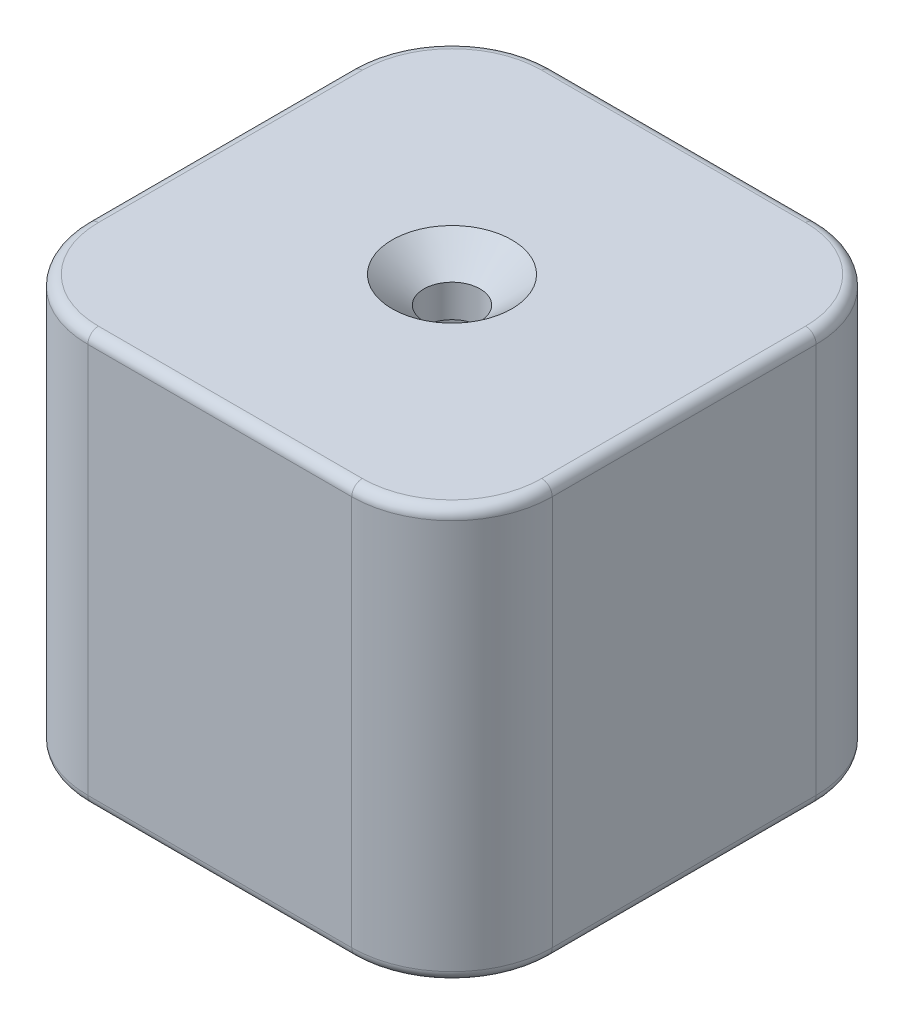
SolidWorks part; units mm, degrees
ref_plane "Front Plane" through (0, 0, 0) normal (0, 0, 1) x (1, 0, 0)
ref_plane "Top Plane" through (0, 0, 0) normal (0, 1, 0) x (1, 0, 0)
ref_plane "Right Plane" through (0, 0, 0) normal (1, 0, 0) x (0, 0, -1)
sketch "Sketch1" plane through (0, 0, 0) normal (0, 1, 0) x (1, 0, 0)
  line L0 (-27.94, -15.875) -> (-27.94, 15.875)
  line L1 (-15.875, -25.4) -> (15.875, -25.4) construction
  line L2 (-25.4, -15.875) -> (-25.4, 15.875) construction
  line L3 (-15.875, 25.4) -> (15.875, 25.4) construction
  line L4 (25.4, -15.875) -> (25.4, 15.875) construction
  line L5 (-25.4, -25.4) -> (25.4, 25.4) construction
  line L6 (-25.4, 25.4) -> (25.4, -25.4) construction
  line L7 (-15.875, 27.94) -> (15.875, 27.94)
  line L8 (27.94, -15.875) -> (27.94, 15.875)
  line L9 (-15.875, -27.94) -> (15.875, -27.94)
  line L10 (-22.86, -15.875) -> (-22.86, 15.875)
  line L11 (-15.875, 22.86) -> (15.875, 22.86)
  line L12 (22.86, -15.875) -> (22.86, 15.875)
  line L13 (-15.875, -22.86) -> (15.875, -22.86)
  arc A0 (-15.875, -25.4) -> (-25.4, -15.875) centre (-15.875, -15.875) cw construction
  arc A1 (15.875, -25.4) -> (25.4, -15.875) centre (15.875, -15.875) ccw construction
  arc A2 (15.875, 25.4) -> (25.4, 15.875) centre (15.875, 15.875) cw construction
  arc A3 (-25.4, 15.875) -> (-15.875, 25.4) centre (-15.875, 15.875) cw construction
  arc A4 (-27.94, 15.875) -> (-15.875, 27.94) centre (-15.875, 15.875) cw
  arc A5 (15.875, 27.94) -> (27.94, 15.875) centre (15.875, 15.875) cw
  arc A6 (15.875, -27.94) -> (27.94, -15.875) centre (15.875, -15.875) ccw
  arc A7 (-15.875, -27.94) -> (-27.94, -15.875) centre (-15.875, -15.875) cw
  arc A8 (-22.86, 15.875) -> (-15.875, 22.86) centre (-15.875, 15.875) cw
  arc A9 (15.875, 22.86) -> (22.86, 15.875) centre (15.875, 15.875) cw
  arc A10 (15.875, -22.86) -> (22.86, -15.875) centre (15.875, -15.875) ccw
  arc A11 (-15.875, -22.86) -> (-22.86, -15.875) centre (-15.875, -15.875) cw
  point P0 (0, 0)
  dimension "D3" = 9.525
  dimension "D1" = 50.8
  dimension "D2" = 50.8
  dimension "D4" = 2.54
  dimension "D5" = 2.54
ref_plane "Plane1" through (0, 43.18, 0) normal (0, 1, 0) x (1, 0, 0)
sketch "Sketch2" plane through (0, 43.18, 0) normal (0, 1, 0) x (1, 0, 0)
  line L4 (-27.94, 15.875) -> (-27.94, -15.875)
  line L5 (15.875, 27.94) -> (-15.875, 27.94)
  line L6 (27.94, -15.875) -> (27.94, 15.875)
  line L7 (-15.875, -27.94) -> (15.875, -27.94)
  line L8 (-27.94, 15.875) -> (-27.94, -15.875)
  line L9 (15.875, 27.94) -> (-15.875, 27.94)
  line L10 (27.94, -15.875) -> (27.94, 15.875)
  line L11 (-15.875, -27.94) -> (15.875, -27.94)
  arc A4 (-15.875, 27.94) -> (-27.94, 15.875) centre (-15.875, 15.875) ccw
  arc A5 (27.94, 15.875) -> (15.875, 27.94) centre (15.875, 15.875) ccw
  arc A6 (15.875, -27.94) -> (27.94, -15.875) centre (15.875, -15.875) ccw
  arc A7 (-27.94, -15.875) -> (-15.875, -27.94) centre (-15.875, -15.875) ccw
  arc A8 (-15.875, 27.94) -> (-27.94, 15.875) centre (-15.875, 15.875) ccw
  arc A9 (27.94, 15.875) -> (15.875, 27.94) centre (15.875, 15.875) ccw
  arc A10 (15.875, -27.94) -> (27.94, -15.875) centre (15.875, -15.875) ccw
  arc A11 (-27.94, -15.875) -> (-15.875, -27.94) centre (-15.875, -15.875) ccw
  dimension "D1" = 0
extrude "Boss-Extrude1" add sketch "Sketch2" against normal blind 0.762 and the other way blind 6.35
extrude "Boss-Extrude2" add sketch "Sketch1" along normal up to surface (42.418 mm away) up to face at (0, 42.418, 0)
sketch "Sketch3" plane through (0, 49.53, 0) normal (0, 1, 0) x (1, 0, 0)
  line L0 (-24.4062, 24.4062) -> (24.4062, -24.4062) construction
  line L4 (-15.875, -27.94) -> (15.875, -27.94)
  line L5 (27.94, -15.875) -> (27.94, 15.875)
  line L6 (15.875, 27.94) -> (-15.875, 27.94)
  line L7 (-27.94, 15.875) -> (-27.94, -15.875)
  line L8 (-15.875, -27.94) -> (15.875, -27.94) construction
  line L9 (27.94, -15.875) -> (27.94, 15.875) construction
  line L10 (15.875, 27.94) -> (-15.875, 27.94) construction
  line L11 (-27.94, 15.875) -> (-27.94, -15.875) construction
  arc A4 (-27.94, -15.875) -> (-15.875, -27.94) centre (-15.875, -15.875) ccw
  arc A5 (15.875, -27.94) -> (27.94, -15.875) centre (15.875, -15.875) ccw
  arc A6 (27.94, 15.875) -> (15.875, 27.94) centre (15.875, 15.875) ccw
  arc A7 (-15.875, 27.94) -> (-27.94, 15.875) centre (-15.875, 15.875) ccw
  arc A8 (-27.94, -15.875) -> (-15.875, -27.94) centre (-15.875, -15.875) ccw construction
  arc A9 (15.875, -27.94) -> (27.94, -15.875) centre (15.875, -15.875) ccw construction
  arc A10 (27.94, 15.875) -> (15.875, 27.94) centre (15.875, 15.875) ccw construction
  arc A11 (-15.875, 27.94) -> (-27.94, 15.875) centre (-15.875, 15.875) ccw construction
  point P10 (0, 0)
  dimension "D1" = 0
hole_wizard "CSK for 1/4 Flat Head Machine Screw (100)1" positions "Sketch4" profile "Sketch5" countersink size "1/4" standard "ANSI Inch" end condition through all
sketch "Sketch4" plane through (0, 49.53, 0) normal (0, 1, 0) x (1, 0, 0)
  point P0 (0, 0)
sketch "Sketch5" plane through (0, 49.53, 0) normal (1, 0, 0) x (0, 0, 1)
  line L0 (0, 0) -> (0, 49.53)
  line L1 (0, 49.53) -> (3.3782, 49.53)
  line L2 (3.3782, 49.53) -> (3.3782, 3.2032)
  line L3 (3.3782, 3.2032) -> (7.1957, 0)
  line L5 (7.1957, 0) -> (0, 0)
  line L6 (-3.3782, 3.2032) -> (-7.1957, 0) construction
  line L11 (0, -6.35) -> (0, 107.95) construction
  dimension "Thru Hole Dia." = 6.7564
  dimension "Thru Hole Depth" = 49.53
  dimension "Near C'Sink Dia." = 14.3913
  dimension "Near C'Sink Angle" = 100
fillet "Fillet1" radius 1.27 8 edges at (24.4062, 49.53, 24.4062) (0, 49.53, 27.94) (-24.4062, 49.53, 24.4062) (-27.94, 49.53, 0) (-24.4062, 49.53, -24.4062) (0, 49.53, -27.94) (24.4062, 49.53, -24.4062) (27.94, 49.53, 0)
chamfer "Chamfer1" distance 1.27 angle 45 8 edges at (0, 0, 22.86) (20.8141, 0, 20.8141) (-20.8141, 0, 20.8141) (22.86, 0, 0) (-22.86, 0, 0) (20.8141, 0, -20.8141) (-20.8141, 0, -20.8141) (0, 0, -22.86)
fillet "Fillet2" radius 1.27 8 edges at (-24.4062, 0, -24.4062) (0, 0, -27.94) (24.4062, 0, -24.4062) (27.94, 0, 0) (24.4062, 0, 24.4062) (0, 0, 27.94) (-24.4062, 0, 24.4062) (-27.94, 0, 0)
